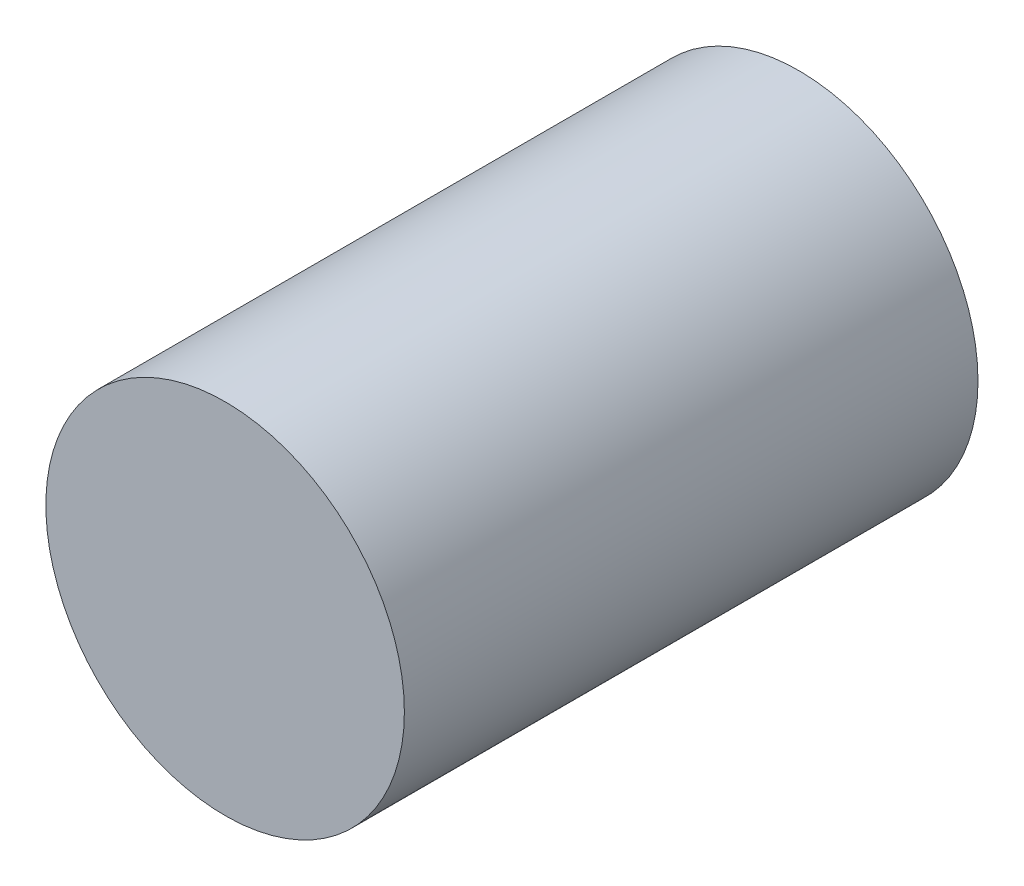
SolidWorks part; units mm, degrees
ref_plane "Ön Düzlem" through (0, 0, 0) normal (0, 0, 1) x (1, 0, 0)
ref_plane "Üst Düzlem" through (0, 0, 0) normal (0, 1, 0) x (1, 0, 0)
ref_plane "Sağ Düzlem" through (0, 0, 0) normal (1, 0, 0) x (0, 0, -1)
sketch "Sketch1" plane through (0, 0, 0) normal (0, 0, 1) x (1, 0, 0)
  circle A0 centre (0, 0) radius 5
  dimension "D1" = 10
extrude "Boss-Extrude1" add sketch "Sketch1" along normal blind 16
